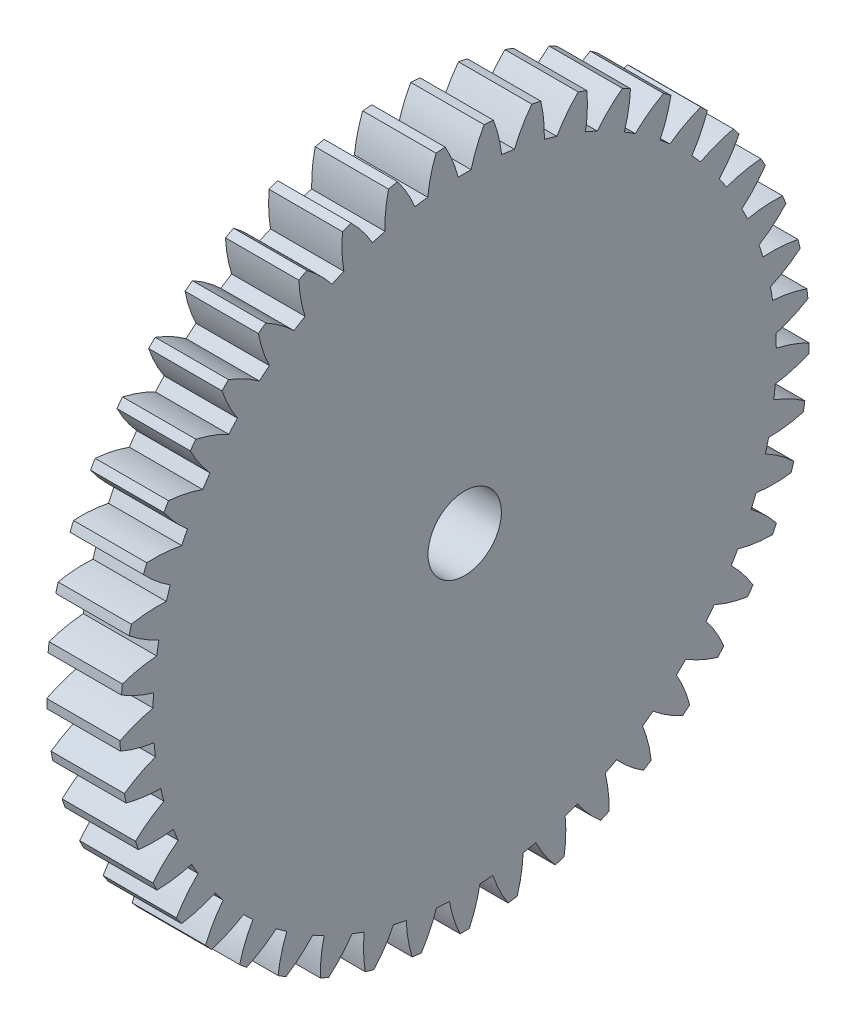
SolidWorks part; units mm, degrees
ref_plane "Plane1" through (0, 0, 0) normal (0, 0, 1) x (1, 0, 0)
ref_plane "Plane2" through (0, 0, 0) normal (0, 1, 0) x (1, 0, 0)
ref_plane "Plane3" through (0, 0, 0) normal (1, 0, 0) x (0, 0, -1)
sketch "HoldingSke" plane through (0, 0, 0) normal (0, 1, 0) x (1, 0, 0)
  line L0 (0, 0) -> (0.7071, -0.7071)
  line L1 (-15, 0) -> (100, 0) construction
  line L2 (0, 0) -> (-2.1039, 2.3779)
  line L3 (0, 0) -> (-11.863, 4.5341)
  line L4 (0, 0) -> (6.1066, 6.1066)
  line L5 (0, 0) -> (-46.8476, -17.4728)
  line L6 (0, 0) -> (-4.1448, -2.7965)
  line L7 (-2.1039, 2.3779) -> (8.6586, 51.2059)
  line L8 (-76.2, 54.61) -> (-75.3, 54.61)
  line L9 (-71.009, 38.7566) -> (-53.1078, 45.2721)
  line L10 (-76.2, 71.12) -> (104.1128, 71.12)
  line L11 (0, 0) -> (-5, 0)
  line L12 (-76.2, 101.6) -> (-76.162, 101.6)
  line L13 (24.9733, 27.94) -> (52.9518, 28.4284)
  line L14 (24.9733, 27.94) -> (24.9743, 27.94)
  line L15 (24.9733, 27.94) -> (100.4006, 29.5858)
  line L16 (-63.627, -1) -> (-12.827, -1)
  circle A0 centre (0, 0) radius 2.5
  circle A1 centre (0, 0) radius 21.249
  circle A2 centre (0, 0) radius 37.5
  circle A3 centre (0, 0) radius 2.5
  dimension "MHD" = 42.498
  dimension "Hub_dia" = 75
  dimension "Bore" = 5
  dimension "MBD" = 5
  dimension "Num_teeth" = 45
  dimension "Pitch" = 1
  dimension "Overall_len" = 50
  dimension "Show_teeth" = 45
  dimension "Thickness" = 5
  dimension "OAL" = 50.0001
  dimension "T_dim" = 0.9
  dimension "Ap" = 20
  dimension "H" = 19.05
  dimension "Pitch_radius" = 180.3128
  dimension "Width" = 5
  dimension "Backlash" = 0.038
  dimension "Addendum_fac" = 1
  dimension "Dedendum_fac" = 1.25
  dimension "Clearance_fac" = 0.25
  dimension "Dedendum_add" = 0.001
  dimension "Module" = 1
sketch "BasProSke" plane through (0, 0, 0) normal (0, 1, 0) x (1, 0, 0)
  line L0 (-10, 0) -> (60, 0) construction
  line L1 (0, 0) -> (0, 23.5)
  line L2 (0, 0) -> (5, 0)
  line L3 (5, 0) -> (5, 23.5)
  line L4 (5, 23.5) -> (0, 23.5)
  dimension "Thickness" = 5
  dimension "Diameter" = 47
revolve "Base-Revolve" add sketch "BasProSke" angle 360 about L0
sketch "TooCutSke" plane through (0, 0, 0) normal (1, 0, 0) x (0, 0, -1)
  line L1 (0, 0) -> (0, 107) construction
  line L2 (0, 0) -> (-0.8517, 22.4839) construction
  line L3 (0, 0) -> (-3.1374, 44.8675) construction
  line L4 (-0.8517, 22.4839) -> (-1.5687, 22.4337) construction
  arc A0 (0.4426, 21.2444) -> (-0.4426, 21.2444) centre (0, 0) ccw
  arc A1 (1.3407, 23.4872) -> (-1.3407, 23.4872) centre (0, 0) ccw
  circle A2 centre (0, 0) radius 22.5 construction
  circle A3 centre (0, 0) radius 21.1431 construction
  arc A4 (-0.4426, 21.2444) -> (-1.3407, 23.4872) centre (-9.1711, 19.0505) ccw
  arc A5 (1.3407, 23.4872) -> (0.4426, 21.2444) centre (9.1711, 19.0505) ccw
  dimension "Root_dia" = 42.498
  dimension "Overcut_dia" = 47.0508
  dimension "Pitch_dia" = 45
  dimension "Base_dia" = 42.2862
  dimension "Flank_rad" = 9
  dimension "Half_ang" = 4
  dimension "Half_CT" = 0.7187
extrude "ToothCut" cut sketch "TooCutSke" along normal through all
fillet "Breaks" [suppressed] radius 0.02
fillet "RootFillets" [suppressed] radius 0.251
pattern_circular "TeethCuts" count 45 every 8 about axis through (-10, 0, 0) along (1, 0, 0) of "ToothCut", "RootFillets", "Breaks"
sketch "HubNeaOneSke" plane through (0, 0, 0) normal (-1, 0, 0) x (0, 0, 1)
  circle A0 centre (0, 0) radius 21.249
  dimension "Diameter" = 42.498
extrude "HubNearOne" [suppressed] add sketch "HubNeaOneSke" along normal blind 45.0001
sketch "HubNeaBotSke" plane through (0, 0, 0) normal (-1, 0, 0) x (0, 0, 1)
  circle A0 centre (0, 0) radius 21.249
  dimension "Diameter" = 42.498
extrude "HubNearBoth" [suppressed] add sketch "HubNeaBotSke" along normal blind 22.5
ref_plane "FarPln" through (5, 0, 0) normal (1, 0, 0) x (0, 0, -1)
sketch "HubFarSke" plane through (5, 0, 0) normal (1, 0, 0) x (0, 0, -1)
  circle A0 centre (0, 0) radius 21.249
  dimension "Diameter" = 42.498
extrude "HubFar" [suppressed] add sketch "HubFarSke" along normal blind 22.5
sketch "BorSke" plane through (0, 0, 0) normal (1, 0, 0) x (0, 0, -1)
  circle A0 centre (0, 0) radius 2.5
  dimension "Diameter" = 5
extrude "Bore" cut sketch "BorSke" along normal mid plane 100.0001
sketch "KeySke" plane through (0, 0, 0) normal (1, 0, 0) x (0, 0, -1)
  line L0 (-1, 0) -> (-1, 3.4)
  line L1 (-1, 3.4) -> (1, 3.4)
  line L2 (1, 3.4) -> (1, 0)
  line L3 (0, 0) -> (0, 34) construction
  line L4 (-1, 0) -> (1, 0)
  dimension "Offset" = 3.4
  dimension "Width" = 2
extrude "Keyway" [suppressed] cut sketch "KeySke" along normal mid plane 100.0001
pattern_circular "Keyway2" [suppressed] count 2 every 90 about axis through (-10, 0, 0) along (1, 0, 0)
equation "' \"Module@HoldingSke\" = 6.35"
equation "' \"Num_teeth@HoldingSke\" = 12"
equation "' \"Ap@HoldingSke\" =  20"
equation "' \"Ap@HoldingSke\" = 20"
equation "' \"Width@HoldingSke\" = 0.5 * 25.4"
equation "' \"Hub_dia@HoldingSke\"= 1 * 25.4"
equation "' \"Hub_dia@HoldingSke\" = 1 * 25.4"
equation "' \"Overall_len@HoldingSke\" = 1.0 * 25.4"
equation "' \"Bore@HoldingSke\" = 0.75 * 25.4"
equation "' \"T_dim@HoldingSke\" = 0.1 * 25.4"
equation "' \"Width@KeySke\" = 0.25 * 25.4"
equation "' \"Show_teeth@HoldingSke\" = 13"
equation "' \"Backlash@HoldingSke\" = 0.009 * 25.4"
equation "' \"Addendum_fac@HoldingSke\" = 1.0"
equation "' \"Dedendum_fac@HoldingSke\" = 1.25"
equation "' \"Dedendum_add@HoldingSke\" = 0.00005 * 25.4"
equation "' \"Clearance_fac@HoldingSke\" = 0.25"
equation "\"Pitch@HoldingSke\" = 1 / \"Module@HoldingSke\""
equation "\"Overcut_dia@TooCutSke\" = (\"Num_teeth@HoldingSke\" + 2 * \"Addendum_fac@HoldingSke\") / \"Pitch@HoldingSke\" + 0.002 * 25.4"
equation "\"Pitch_dia@TooCutSke\" = \"Num_teeth@HoldingSke\" / \"Pitch@HoldingSke\""
equation "\"Base_dia@TooCutSke\" = \"Num_teeth@HoldingSke\" / \"Pitch@HoldingSke\" * cos((\"Ap@HoldingSke\"  * 3.14159265 / 180))"
equation "\"Root_dia@TooCutSke\" = (\"Num_teeth@HoldingSke\" + 2) / \"Pitch@HoldingSke\" - 2 * (\"Addendum_fac@HoldingSke\" + \"Dedendum_fac@HoldingSke\") / \"Pitch@HoldingSke\" - \"Dedendum_add@HoldingSke\" * 2"
equation "\"Half_ang@TooCutSke\" = 180 / \"Num_teeth@HoldingSke\""
equation "\"Half_CT@TooCutSke\" = \"Num_teeth@HoldingSke\" / \"Pitch@HoldingSke\" * sin((3.14159265 / 2 / \"Num_teeth@HoldingSke\")) / 2 - 7 * \"Backlash@HoldingSke\" / 4"
equation "\"Flank_rad@TooCutSke\" = \"Num_teeth@HoldingSke\" / \"Pitch@HoldingSke\" / 5"
equation "\"Radius@RootFillets\" = \"Clearance_fac@HoldingSke\" / \"Pitch@HoldingSke\" + \"Dedendum_add@HoldingSke\""
equation "\"Break_rad@Breaks\" = 0.02 / \"Pitch@HoldingSke\""
equation "\"Thickness@HoldingSke\" = \"Width@HoldingSke\""
equation "\"OAL@HoldingSke\" = \"Thickness@HoldingSke\""
equation "\"MHD@HoldingSke\" = (\"Num_teeth@HoldingSke\" + 2) / \"Pitch@HoldingSke\" - 2 * (\"Addendum_fac@HoldingSke\" + \"Dedendum_fac@HoldingSke\")  / \"Pitch@HoldingSke\" - \"Dedendum_add@HoldingSke\" * 2"
equation "\"MBD@HoldingSke\" = (\"Num_teeth@HoldingSke\" + 2) / \"Pitch@HoldingSke\" - 2 * (\"Addendum_fac@HoldingSke\" + \"Dedendum_fac@HoldingSke\")  / \"Pitch@HoldingSke\" - \"Dedendum_add@HoldingSke\" * 2 - 0.002 * 25.4"
equation "\"MHD@HoldingSke\" = ((sgn( \"MHD@HoldingSke\" - \"Hub_dia@HoldingSke\" )-1)*( \"MHD@HoldingSke\" - \"Hub_dia@HoldingSke\" ))/-2+ \"Hub_dia@HoldingSke\""
equation "\"MBD@HoldingSke\" = ((sgn( \"MBD@HoldingSke\" - \"Bore@HoldingSke\" )-1)*( \"MBD@HoldingSke\" - \"Bore@HoldingSke\" ))/-2+ \"Bore@HoldingSke\""
equation "\"OAL@HoldingSke\" = ((sgn( \"OAL@HoldingSke\" - \"Overall_len@HoldingSke\" )+1)*( \"OAL@HoldingSke\" - \"Overall_len@HoldingSke\" ))/2 + \"Overall_len@HoldingSke\" + 0.000002 * 25.4"
equation "\"Num_teeth@TeethCuts\" = int( \"Show_teeth@HoldingSke\" ) + 1"
equation "\"Num_teeth@TeethCuts\" = ((sgn( \"Num_teeth@TeethCuts\" - \"Num_teeth@HoldingSke\" )-1)*( \"Num_teeth@TeethCuts\" - \"Num_teeth@HoldingSke\" ))/-2+ \"Num_teeth@HoldingSke\""
equation "\"Num_teeth@TeethCuts\" = ((sgn( \"Num_teeth@TeethCuts\" - 2.0)+1)*( \"Num_teeth@TeethCuts\" - 2.0))/2 +2.0"
equation "\"Angle@TeethCuts\" = 360.0 / \"Num_teeth@HoldingSke\""
equation "\"Diameter@BasProSke\" = (\"Num_teeth@HoldingSke\" + 2 * \"Addendum_fac@HoldingSke\") / \"Pitch@HoldingSke\""
equation "\"Thickness@BasProSke\"  = \"Thickness@HoldingSke\""
equation "' \"Fillet_rad@BasProSke\" =  \"Thickness@HoldingSke\" * 0.05"
equation "' \"Fillet_rad@BasProSke\" = \"Thickness@HoldingSke\" * 0.05"
equation "\"MHD@HoldingSke\" = ((sgn( \"MHD@HoldingSke\" - \"Root_dia@TooCutSke\" )-1)*( \"MHD@HoldingSke\" - \"Root_dia@TooCutSke\" ))/-2+ \"Root_dia@TooCutSke\""
equation "\"Diameter@HubNeaOneSke\" = \"MHD@HoldingSke\""
equation "\"Length@HubNearOne\" = \"OAL@HoldingSke\" - \"Thickness@BasProSke\""
equation "\"Diameter@HubNeaBotSke\" = \"MHD@HoldingSke\""
equation "\"Length@HubNearBoth\" = ( \"OAL@HoldingSke\" - \"Thickness@BasProSke\" ) / 2.0"
equation "\"Thickness@FarPln\" = \"Thickness@BasProSke\""
equation "\"Diameter@HubFarSke\" = \"MHD@HoldingSke\""
equation "\"Length@HubFar\" = ( \"OAL@HoldingSke\" - \"Thickness@BasProSke\" ) / 2.0"
equation "\"Diameter@BorSke\" = \"MBD@HoldingSke\""
equation "\"D1@Bore\" = \"OAL@HoldingSke\" * 2.0"
equation "\"D1@Keyway\" = \"OAL@HoldingSke\" * 2.0"
equation "\"Offset@KeySke\" = \"T_dim@HoldingSke\" + \"MBD@HoldingSke\" / 2.0"
